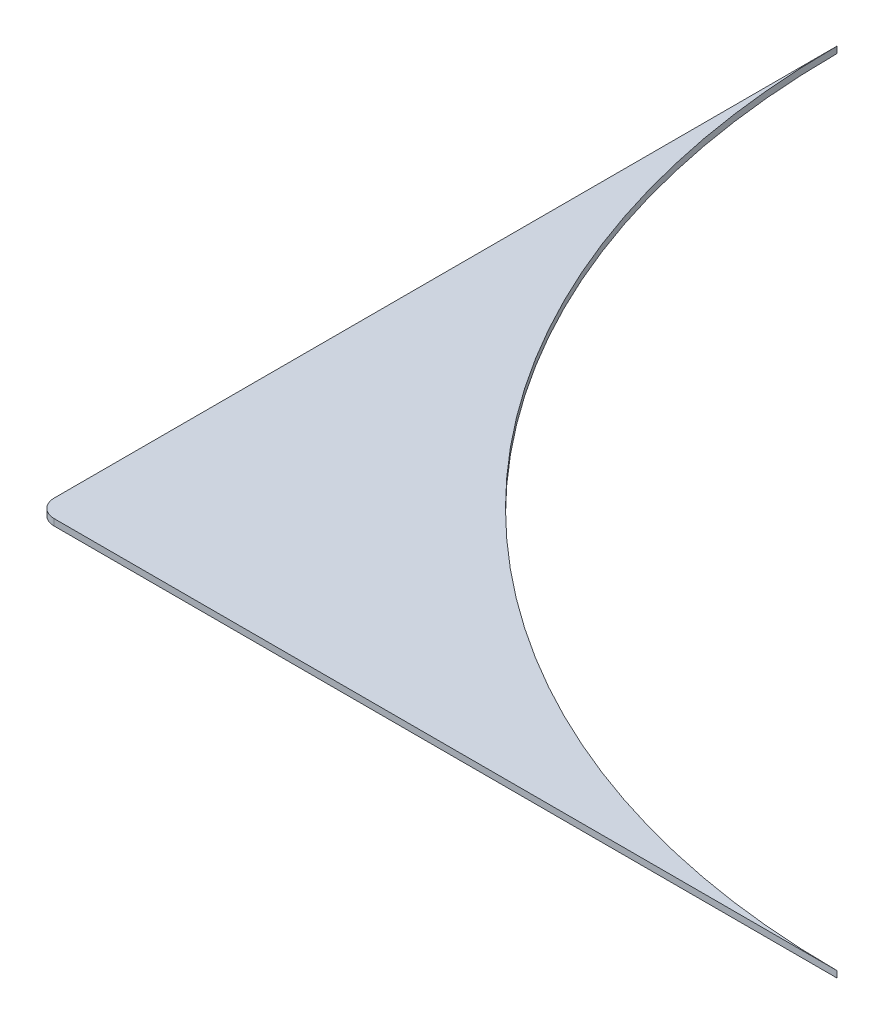
SolidWorks part; units mm, degrees
material "AISI 1020"
ref_plane "Front Plane" through (0, 0, 0) normal (0, 0, 1) x (1, 0, 0)
ref_plane "Top Plane" through (0, 0, 0) normal (0, 1, 0) x (1, 0, 0)
ref_plane "Right Plane" through (0, 0, 0) normal (1, 0, 0) x (0, 0, -1)
sketch "Sketch1" plane through (0, 0, 0) normal (0, 1, 0) x (1, 0, 0)
  line L0 (-152.4, 0) -> (-152.4, -184.209)
  line L1 (-148.209, -188.4) -> (35.941, -188.4)
  arc A0 (-152.4, 0) -> (35.941, -188.4) centre (36, 0) ccw
  arc A1 (-152.4, -184.209) -> (-148.209, -188.4) centre (-148.209, -184.209) ccw
  dimension "D1" = 184.15
  dimension "D3" = 8.382
  dimension "D2" = 184.209
extrude "Boss-Extrude1" add sketch "Sketch1" along normal blind 1.524
